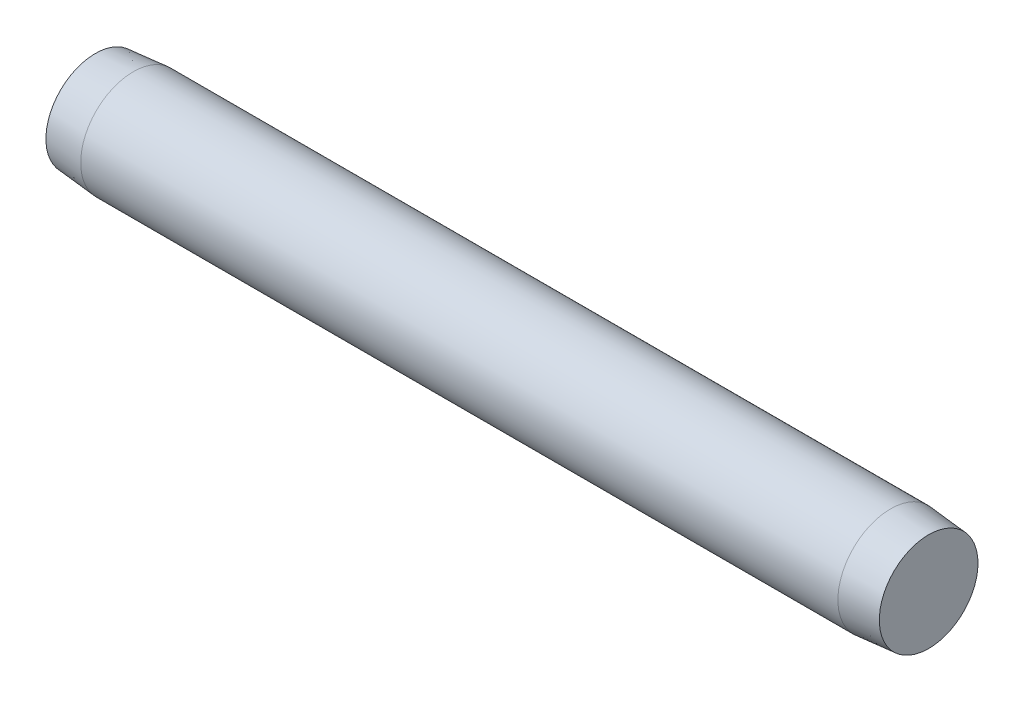
SolidWorks part; units mm, degrees
ref_plane "Front Plane" through (0, 0, 0) normal (0, 0, 1) x (1, 0, 0)
ref_plane "Top Plane" through (0, 0, 0) normal (0, 1, 0) x (1, 0, 0)
ref_plane "Right Plane" through (0, 0, 0) normal (1, 0, 0) x (0, 0, -1)
sketch "Sketch1" plane through (0, 0, 0) normal (1, 0, 0) x (0, 0, -1)
  circle A0 centre (0, 0) radius 1.58
  dimension "D1" = 3.16
extrude "Boss-Extrude1" add sketch "Sketch1" along normal blind 25
chamfer "Chamfer1" distance 0.1 angle 85 1 edges at (0, 0, -1.58)
chamfer "Chamfer2" distance 0.1 angle 85 1 edges at (25, 0, -1.58)
